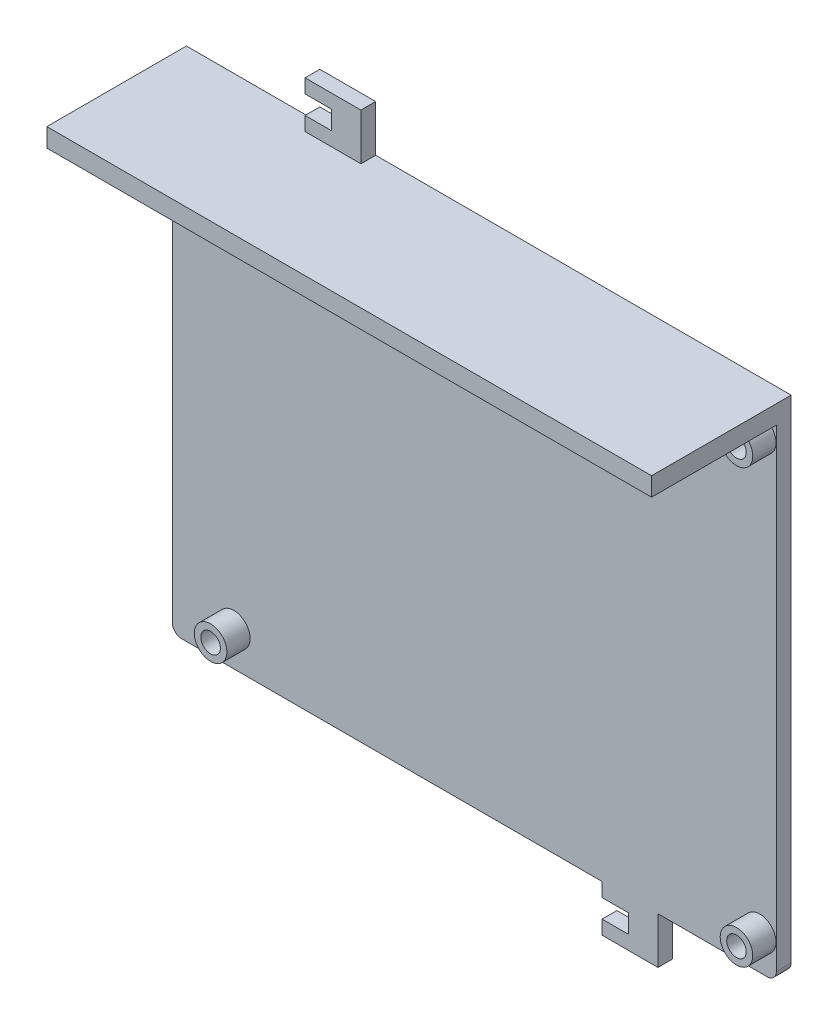
SolidWorks part; units mm, degrees
material "Custom Plastic"
ref_plane "X-Y Datum" through (0, 0, 0) normal (0, 0, 1) x (1, 0, 0)
ref_plane "X-Z Datum" through (0, 0, 0) normal (0, 1, 0) x (1, 0, 0)
ref_plane "Y-Z Datum" through (0, 0, 0) normal (1, 0, 0) x (0, 0, -1)
sketch "Sketch1" plane through (0, 0, -78.1448) normal (0, 0, -1) x (-1, 0, 0)
  circle A0 centre (153.1236, -95.3154) radius 2.1 construction
  circle A1 centre (266.1536, -95.3154) radius 2.1 construction
  circle A2 centre (153.1236, -95.3154) radius 2.1
  circle A3 centre (266.1536, -95.3154) radius 2.1
  circle A4 centre (266.1536, -2.3514) radius 2.1 construction
  circle A5 centre (153.1236, -2.3514) radius 2.1 construction
  circle A6 centre (266.1536, -2.3514) radius 2.1
  circle A7 centre (153.1236, -2.3514) radius 2.1
  circle A8 centre (153.1236, -2.3514) radius 3.5
  circle A9 centre (266.1536, -2.3514) radius 3.5
  circle A10 centre (153.1236, -95.3154) radius 3.5
  circle A11 centre (266.1536, -95.3154) radius 3.5
  dimension "D1" = 7
  dimension "D2" = 7
  dimension "D3" = 7
  dimension "D4" = 7
extrude "Boss-Extrude1" add sketch "Sketch1" along normal blind 5
sketch "Sketch2" plane through (0, 0, -83.1448) normal (0, 0, -1) x (-1, 0, 0)
  line L0 (214.4646, 1.7126) -> (214.4646, -103.4434) construction
  line L1 (277.5836, 1.7126) -> (151.3456, 1.7126) construction
  line L2 (151.3456, -103.4434) -> (277.5836, -103.4434) construction
  line L3 (148.8056, -50.9289) -> (280.1236, -50.8654) construction
  line L4 (148.8056, -0.9544) -> (148.8056, -100.9034) construction
  line L5 (280.1236, -100.9034) -> (280.1236, -0.8274) construction
  line L7 (149.5496, -102.6994) -> (279.3796, -102.6994)
  line L8 (149.5496, -102.6994) -> (149.5496, 0.9686)
  line L9 (149.5496, 0.9686) -> (279.3796, 0.9686)
  line L10 (279.3796, -102.6994) -> (279.3796, 0.9686)
  line L11 (149.5496, -102.6994) -> (279.3796, 0.9686) construction
  line L12 (149.5496, 0.9686) -> (279.3796, -102.6994) construction
  arc A0 (280.1236, -0.8274) -> (277.5836, 1.7126) centre (277.5834, -0.8276) ccw construction
  point P12 (214.4646, -50.8654)
extrude "Boss-Extrude2" add sketch "Sketch2" along normal blind 3.175
sketch "Sketch3" plane through (0, 0, -86.3198) normal (0, 0, -1) x (-1, 0, 0)
  line L1 (149.5496, 0.9686) -> (279.5222, 0.9686)
  line L2 (149.5496, 0.9686) -> (149.5496, 4.9686)
  line L3 (149.5496, 4.9686) -> (279.5222, 4.9686)
  line L4 (279.5222, 0.9686) -> (279.5222, 4.9686)
  arc A0 (151.3456, 1.7126) -> (148.8056, -0.8274) centre (151.3458, -0.8276) ccw construction
  dimension "D1" = 129.9726
  dimension "D2" = 4
extrude "Boss-Extrude3" add sketch "Sketch3" against normal blind 30
fillet "Fillet1" radius 2 2 edges at (-279.3796, -102.6994, -84.7323) (-149.5496, -102.6994, -84.7323)
sketch "Sketch4" plane through (0, 0, -86.3198) normal (0, 0, -1) x (-1, 0, 0)
  line L0 (238.8517, 4.9686) -> (238.8517, 14.9686)
  line L1 (279.5222, 4.9686) -> (149.5496, 4.9686) construction
  line L2 (238.8517, 14.9686) -> (250.8517, 14.9686)
  line L3 (250.8517, 14.9686) -> (250.8517, 11.9686)
  line L4 (250.8517, 11.9686) -> (245.2017, 11.9686)
  line L5 (245.2017, 11.9686) -> (245.2017, 7.9686)
  line L6 (245.2017, 7.9686) -> (250.8517, 7.9686)
  line L7 (250.8517, 7.9686) -> (250.8517, 4.9686)
  line L8 (279.5222, 4.9686) -> (250.8517, 4.9686)
  line L9 (238.8517, 4.9686) -> (250.8517, 4.9686)
  line L10 (175.0025, -102.6994) -> (175.0025, -112.6994)
  line L11 (175.0025, -112.6994) -> (187.0025, -112.6994)
  line L12 (187.0025, -112.6994) -> (187.0025, -109.6994)
  line L13 (187.0025, -109.6994) -> (181.3525, -109.6994)
  line L14 (151.5496, -102.6994) -> (277.3796, -102.6994)
  line L15 (279.3796, -100.6994) -> (279.3796, 0.9686)
  line L16 (279.3796, 0.9686) -> (279.5222, 0.9686)
  line L17 (279.5222, 0.9686) -> (279.5222, 4.9686)
  line L18 (279.5222, 4.9686) -> (149.5496, 4.9686)
  line L19 (149.5496, 4.9686) -> (149.5496, -100.6994)
  line L20 (151.5496, -102.6994) -> (277.3796, -102.6994)
  line L21 (279.3796, -100.6994) -> (279.3796, 0.9686)
  line L22 (279.3796, 0.9686) -> (279.5222, 0.9686)
  line L23 (279.5222, 0.9686) -> (279.5222, 4.9686)
  line L24 (238.8517, 4.9686) -> (149.5496, 4.9686)
  line L25 (149.5496, 4.9686) -> (149.5496, -100.6994)
  line L26 (181.3525, -109.6994) -> (181.3525, -105.6994)
  line L27 (181.3525, -105.6994) -> (187.0025, -105.6994)
  line L28 (187.0025, -105.6994) -> (187.0025, -102.6994)
  line L29 (187.0025, -102.6994) -> (175.0025, -102.6994)
  line L30 (175.0025, -102.6994) -> (187.0025, -102.6994)
  arc A2 (277.3796, -102.6994) -> (279.3796, -100.6994) centre (277.3796, -100.6994) ccw
  arc A3 (149.5496, -100.6994) -> (151.5496, -102.6994) centre (151.5496, -100.6994) ccw
  arc A4 (277.3796, -102.6994) -> (279.3796, -100.6994) centre (277.3796, -100.6994) ccw
  arc A5 (149.5496, -100.6994) -> (151.5496, -102.6994) centre (151.5496, -100.6994) ccw
  line M13 (151.5496, -102.6994) -> (277.3796, -102.6994)
  line M18 (279.5222, 4.9686) -> (149.5496, 4.9686)
  dimension "D1" = 10
  dimension "D2" = 4
  dimension "D3" = 3
  dimension "D4" = 6.35
  dimension "D5" = 0
  dimension "D6" = 12
  dimension "D7" = 6.35
extrude "Boss-Extrude4" add sketch "Sketch4" against normal blind 3.175 contours L7 L6 L5 L4 L3 L2 L0 M18 | L27 L28 L10 L11 L12 L13 L26 M13
